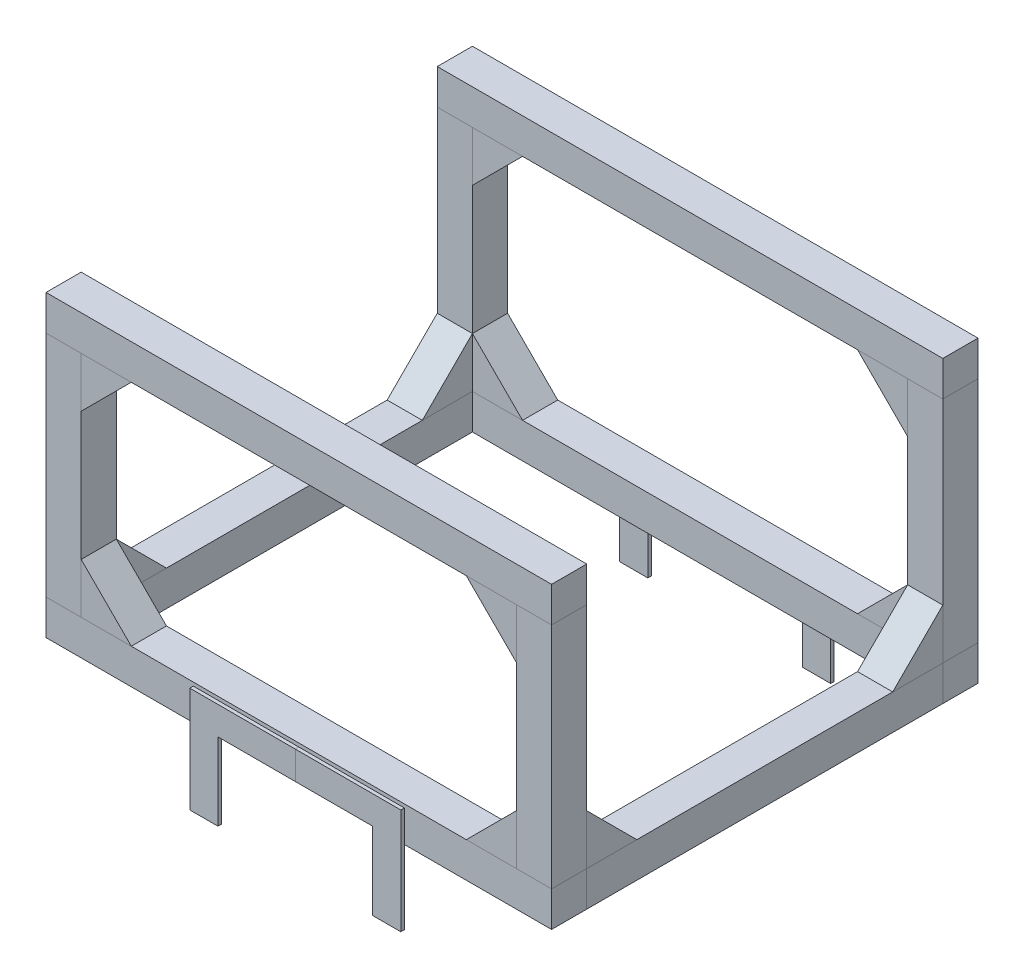
SolidWorks part; units mm, degrees
ref_plane "Front Plane" through (0, 0, 0) normal (0, 0, 1) x (1, 0, 0)
ref_plane "Top Plane" through (0, 0, 0) normal (0, 1, 0) x (1, 0, 0)
ref_plane "Right Plane" through (0, 0, 0) normal (1, 0, 0) x (0, 0, -1)
sketch "Sketch1" plane through (0, 0, 0) normal (0, 0, 1) x (1, 0, 0)
  line L0 (0, 0) -> (267.5, 0) construction
  line L1 (-10, 10) -> (10, 10)
  line L2 (-10, 10) -> (-10, -10)
  line L3 (-10, -10) -> (10, -10)
  line L4 (10, 10) -> (10, -10)
  line L5 (-10, 10) -> (10, -10) construction
  line L6 (-10, -10) -> (10, 10) construction
  line L8 (277.5, 10) -> (257.5, 10)
  line L9 (277.5, 10) -> (277.5, -10)
  line L10 (277.5, -10) -> (257.5, -10)
  line L11 (257.5, 10) -> (257.5, -10)
  line L12 (277.5, 10) -> (257.5, -10) construction
  line L13 (277.5, -10) -> (257.5, 10) construction
  point P0 (0, 0)
  point P12 (-267.5, 0)
  point P13 (67.677, 0)
  point P14 (10, 0)
  point P15 (0, 0)
  dimension "D1" = 20
  dimension "D2" = 20
  dimension "D3" = 267.5
  dimension "D4" = 20
  dimension "D5" = 20
extrude "Boss-Extrude1" add sketch "Sketch1" along normal mid plane 202.5
sketch "Sketch2" plane through (-10, 0, 0) normal (-1, 0, 0) x (0, 0, 1)
  line L0 (101.25, 10) -> (101.25, -10)
  line L1 (101.25, 10) -> (121.25, 10)
  line L2 (101.25, -10) -> (121.25, -10)
  line L3 (121.25, 10) -> (121.25, -10)
  line L4 (-101.25, 10) -> (-101.25, -10)
  line L5 (-101.25, 10) -> (-121.25, 10)
  line L6 (-101.25, -10) -> (-121.25, -10)
  line L7 (-121.25, 10) -> (-121.25, -10)
  dimension "D1" = 20
  dimension "D2" = 20
extrude "Boss-Extrude2" add sketch "Sketch2" against normal blind 287.5 separate body
sketch "Sketch4" plane through (0, 10, 0) normal (0, 1, 0) x (1, 0, 0)
  line L0 (10, 101.25) -> (10, 121.25)
  line L1 (10, 101.25) -> (-10, 101.25)
  line L2 (10, 121.25) -> (-10, 121.25)
  line L3 (-10, 101.25) -> (-10, 121.25)
  line L4 (277.5, 121.25) -> (-10, 121.25) construction
  line L6 (10, -101.25) -> (10, -121.25)
  line L7 (10, -101.25) -> (-10, -101.25)
  line L8 (10, -121.25) -> (-10, -121.25)
  line L9 (-10, -101.25) -> (-10, -121.25)
  line L10 (277.5, -121.25) -> (-10, -121.25) construction
  line L12 (277.5, -121.25) -> (277.5, -101.25)
  line L13 (277.5, -121.25) -> (257.5, -121.25)
  line L14 (277.5, -101.25) -> (257.5, -101.25)
  line L15 (257.5, -121.25) -> (257.5, -101.25)
  line L16 (277.5, 101.25) -> (277.5, 121.25)
  line L17 (277.5, 101.25) -> (257.5, 101.25)
  line L18 (277.5, 121.25) -> (257.5, 121.25)
  line L19 (257.5, 101.25) -> (257.5, 121.25)
  dimension "D1" = 20
  dimension "D2" = 20
  dimension "D3" = 20
  dimension "D4" = 20
extrude "Boss-Extrude3" add sketch "Sketch4" along normal blind 130 separate body
sketch "Sketch5" plane through (-10, 0, 0) normal (-1, 0, 0) x (0, 0, 1)
  line L0 (-121.25, 140) -> (-101.25, 140)
  line L1 (-121.25, 140) -> (-121.25, 160)
  line L2 (-101.25, 140) -> (-101.25, 160)
  line L3 (-121.25, 160) -> (-101.25, 160)
  line L4 (101.25, 140) -> (121.25, 140)
  line L5 (101.25, 140) -> (101.25, 160)
  line L6 (121.25, 140) -> (121.25, 160)
  line L7 (101.25, 160) -> (121.25, 160)
  dimension "D1" = 20
  dimension "D2" = 20
extrude "Boss-Extrude4" add sketch "Sketch5" against normal blind 287.5 separate body
sketch "Sketch6" plane through (277.5, 0, 0) normal (1, 0, 0) x (0, 0, -1)
  line L0 (-101.25, 10) -> (-72.75, 10)
  line L1 (-101.25, 10) -> (101.25, 10) construction
  line L2 (-72.75, 10) -> (-101.25, 38.5)
  line L3 (-101.25, 140) -> (-101.25, 10) construction
  line L4 (-101.25, 38.5) -> (-101.25, 10)
  line L5 (101.25, 10) -> (72.75, 10)
  line L6 (72.75, 10) -> (101.25, 38.5)
  line L7 (101.25, 38.5) -> (101.25, 10)
  dimension "D1" = 28.5
  dimension "D2" = 28.5
  dimension "D3" = 28.5
  dimension "D4" = 28.5
extrude "Boss-Extrude5" add sketch "Sketch6" against normal blind 20 separate body
sketch "Sketch7" plane through (-10, 0, 0) normal (-1, 0, 0) x (0, 0, 1)
  line L0 (-101.25, 10) -> (-101.25, 38.5)
  line L1 (-101.25, 38.5) -> (-72.75, 10)
  line L2 (-72.75, 10) -> (-101.25, 10)
  line L3 (101.25, 10) -> (101.25, 38.5)
  line L4 (101.25, 38.5) -> (72.75, 10)
  line L5 (72.75, 10) -> (101.25, 10)
extrude "Boss-Extrude6" add sketch "Sketch7" against normal blind 20 separate body
sketch "Sketch8" plane through (0, 0, 121.25) normal (0, 0, 1) x (1, 0, 0)
  line L0 (10, 10) -> (10, 38.5)
  line L1 (10, 38.5) -> (38.5, 10)
  line L2 (277.5, 10) -> (-10, 10) construction
  line L3 (38.5, 10) -> (10, 10)
  line L4 (10, 140) -> (10, 111.5)
  line L5 (10, 140) -> (10, 10) construction
  line L6 (10, 111.5) -> (38.5, 140)
  line L7 (277.5, 140) -> (-10, 140) construction
  line L8 (38.5, 140) -> (10, 140)
  line L9 (257.5, 140) -> (257.5, 111.5)
  line L10 (257.5, 140) -> (257.5, 10) construction
  line L11 (257.5, 111.5) -> (229, 140)
  line L12 (229, 140) -> (257.5, 140)
  line L13 (257.5, 10) -> (257.5, 38.5)
  line L14 (257.5, 38.5) -> (229, 10)
  line L15 (229, 10) -> (257.5, 10)
  dimension "D1" = 28.5
  dimension "D2" = 28.5
  dimension "D3" = 28.5
  dimension "D4" = 28.5
  dimension "D5" = 28.5
  dimension "D6" = 28.5
  dimension "D7" = 28.5
extrude "Boss-Extrude7" add sketch "Sketch8" against normal blind 20 separate body
sketch "Sketch9" plane through (0, 0, -121.25) normal (0, 0, -1) x (-1, 0, 0)
  line L0 (-229, 10) -> (-257.5, 10) construction
  line L1 (-257.5, 10) -> (-257.5, 38.5) construction
  line L2 (-257.5, 38.5) -> (-229, 10) construction
  line L3 (-38.5, 10) -> (-10, 10) construction
  line L4 (-10, 10) -> (-10, 38.5) construction
  line L5 (-10, 38.5) -> (-38.5, 10) construction
  line L6 (-10, 140) -> (-10, 111.5) construction
  line L7 (-10, 111.5) -> (-38.5, 140) construction
  line L8 (-38.5, 140) -> (-10, 140) construction
  line L9 (-229, 140) -> (-257.5, 140) construction
  line L10 (-257.5, 111.5) -> (-229, 140) construction
  line L11 (-257.5, 140) -> (-257.5, 111.5) construction
  line L12 (-229, 10) -> (-257.5, 10)
  line L13 (-257.5, 10) -> (-257.5, 38.5)
  line L14 (-257.5, 38.5) -> (-229, 10)
  line L15 (-38.5, 10) -> (-10, 10)
  line L16 (-10, 10) -> (-10, 38.5)
  line L17 (-10, 38.5) -> (-38.5, 10)
  line L18 (-10, 140) -> (-10, 111.5)
  line L19 (-10, 111.5) -> (-38.5, 140)
  line L20 (-38.5, 140) -> (-10, 140)
  line L21 (-229, 140) -> (-257.5, 140)
  line L22 (-257.5, 111.5) -> (-229, 140)
  line L23 (-257.5, 140) -> (-257.5, 111.5)
extrude "Boss-Extrude8" add sketch "Sketch9" against normal blind 20 separate body
sketch "Sketch10" plane through (0, 0, -121.25) normal (0, 0, -1) x (-1, 0, 0)
  line L0 (10, 0) -> (-277.5, 0) construction
  line L1 (10, 10) -> (10, -10) construction
  line L2 (-277.5, 10) -> (-277.5, -10) construction
  line L3 (-133.75, 8) -> (-133.75, -8)
  line L4 (-133.75, 8) -> (-73.75, 8)
  line L5 (-73.75, 8) -> (-73.75, -52)
  line L6 (-73.75, -52) -> (-89.75, -52)
  line L7 (-89.75, -52) -> (-89.75, -8)
  line L8 (-89.75, -8) -> (-133.75, -8)
  line L9 (-133.75, -8) -> (-133.75, -39.4625) construction
  point P10 (-133.75, 0)
  point P11 (-133.75, 0)
  dimension "D1" = 16
  dimension "D2" = 16
  dimension "D3" = 60
  dimension "D4" = 60
extrude "Boss-Extrude9" add sketch "Sketch10" along normal blind 2 separate body
sketch "Sketch11" plane through (0, 0, -121.25) normal (0, 0, -1) x (-1, 0, 0)
  line L4 (-133.75, 8) -> (-73.75, 8) construction
  line L5 (-133.75, 8) -> (-133.75, -8) construction
  line L6 (-89.75, -8) -> (-133.75, -8) construction
  line L11 (-193.75, 8) -> (-133.75, 8)
  line L12 (-133.75, 8) -> (-133.75, -8)
  line L13 (-133.75, -8) -> (-177.75, -8)
  line L14 (-193.75, 8) -> (-193.75, -52)
  line L15 (-193.75, -52) -> (-177.75, -52)
  line L16 (-177.75, -52) -> (-177.75, -8)
extrude "Boss-Extrude10" add sketch "Sketch11" along normal blind 2 separate body
sketch "Sketch12" plane through (0, 0, 121.25) normal (0, 0, 1) x (1, 0, 0)
  line L0 (133.75, 8) -> (133.75, -8)
  line L1 (133.75, -8) -> (177.75, -8)
  line L2 (177.75, -8) -> (177.75, -52)
  line L3 (177.75, -52) -> (193.75, -52)
  line L4 (193.75, -52) -> (193.75, 8)
  line L5 (193.75, 8) -> (133.75, 8)
extrude "Boss-Extrude11" add sketch "Sketch12" along normal blind 2 separate body
sketch "Sketch13" plane through (0, 0, 121.25) normal (0, 0, 1) x (1, 0, 0)
  line L0 (73.75, 8) -> (73.75, -52) construction
  line L1 (73.75, -52) -> (89.75, -52) construction
  line L2 (89.75, -52) -> (89.75, -8) construction
  line L3 (89.75, -8) -> (133.75, -8) construction
  line L4 (133.75, 8) -> (133.75, -8) construction
  line L5 (133.75, 8) -> (73.75, 8) construction
  line L6 (73.75, 8) -> (73.75, -52)
  line L7 (73.75, -52) -> (89.75, -52)
  line L8 (89.75, -52) -> (89.75, -8)
  line L9 (89.75, -8) -> (133.75, -8)
  line L10 (133.75, 8) -> (133.75, -8)
  line L11 (133.75, 8) -> (73.75, 8)
extrude "Boss-Extrude12" add sketch "Sketch13" along normal blind 2 separate body
